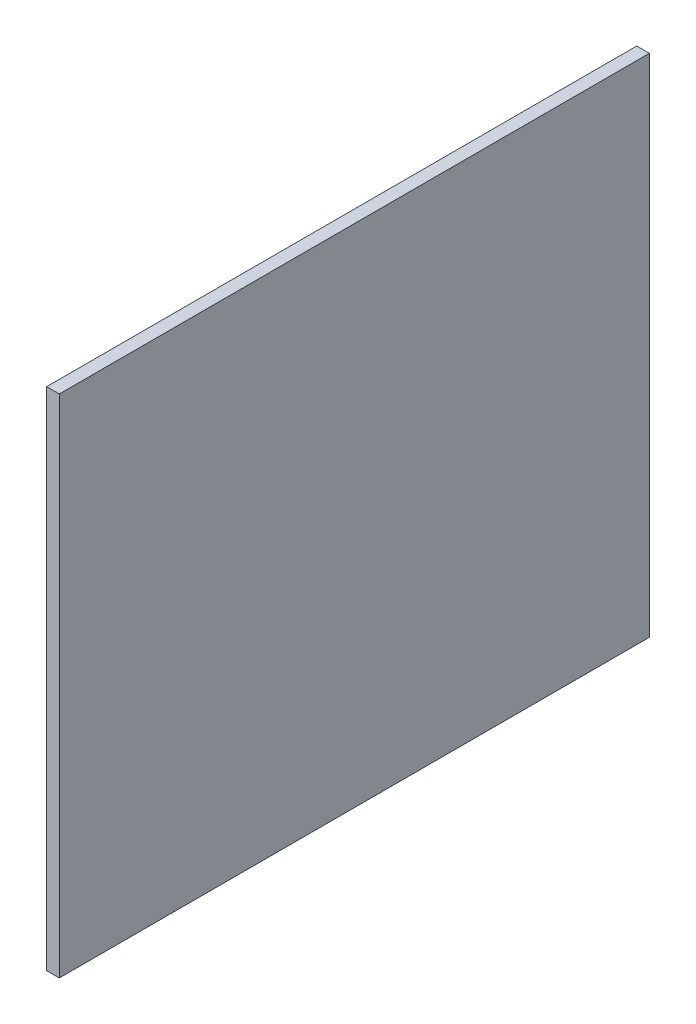
SolidWorks part; units mm, degrees
material "Beech"
ref_plane "Front Plane" through (0, 0, 0) normal (1, 0, 0) x (0, 1, 0)
ref_plane "Top Plane" through (0, 0, 0) normal (0, 0, 1) x (0, 1, 0)
ref_plane "Right Plane" through (0, 0, 0) normal (0, 1, 0) x (-1, 0, 0)
sketch "Sketch1" plane through (0, 0, 0) normal (1, 0, 0) x (0, 1, 0)
  line L1 (0, 0) -> (120, 0)
  line L2 (0, 0) -> (0, 140)
  line L3 (0, 140) -> (120, 140)
  line L4 (120, 0) -> (120, 140)
  dimension "D1" = 140
  dimension "D2" = 120
extrude "Boss-Extrude1" add sketch "Sketch1" along normal blind 3
